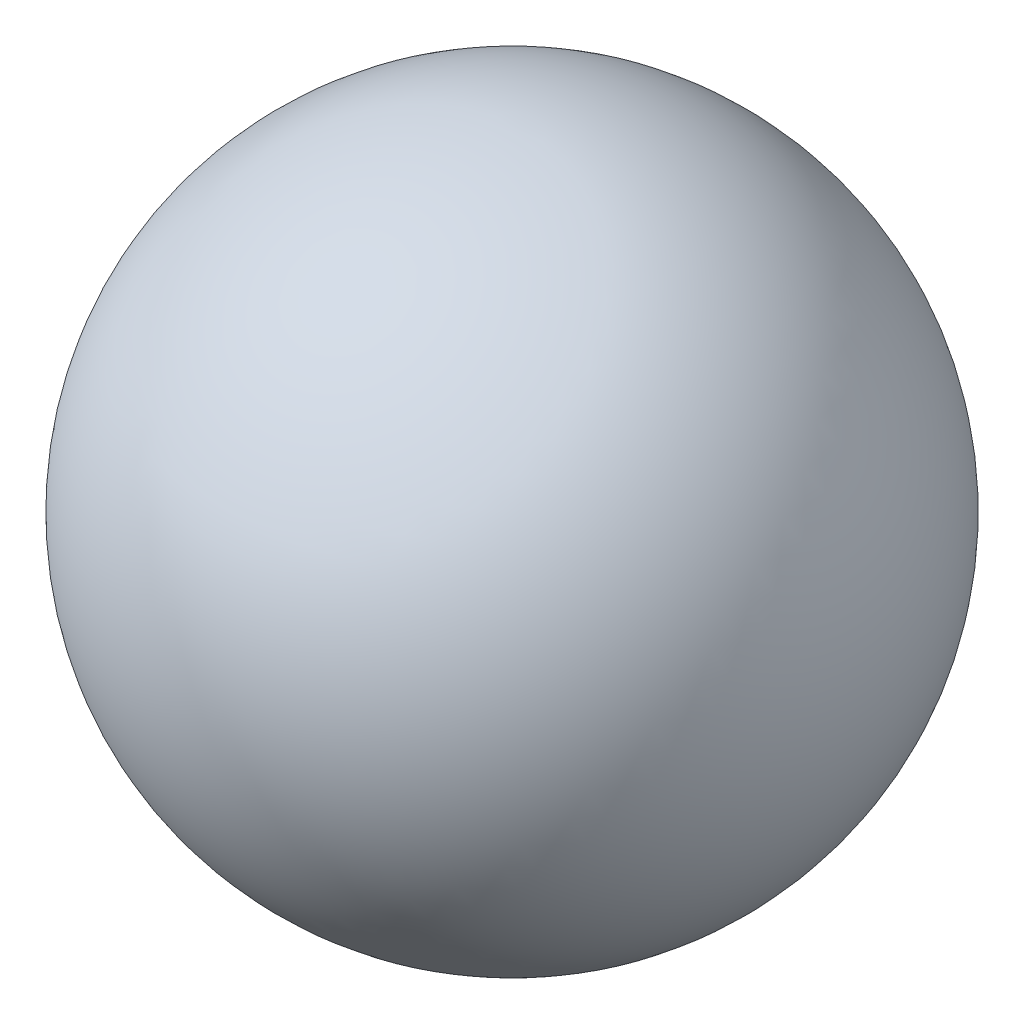
SolidWorks part; units mm, degrees
ref_plane "Front" through (0, 0, 0) normal (0, 0, 1) x (1, 0, 0)
ref_plane "Top" through (0, 0, 0) normal (0, 1, 0) x (1, 0, 0)
ref_plane "Right" through (0, 0, 0) normal (1, 0, 0) x (0, 0, -1)
sketch "Sketch1" plane through (0, 0, 0) normal (0, 0, 1) x (1, 0, 0)
  line L0 (-6, 6) -> (6, 6)
  line L1 (-6, 0) -> (6, 0)
  line L2 (-6, 0) -> (-6, 18)
  line L3 (-6, 18) -> (6, 18)
  line L4 (6, 0) -> (6, 18)
  line L5 (-6, 18) -> (6, 6)
  line L6 (-6, 15) -> (6, 15)
  line L7 (-6, 9) -> (6, 9)
  circle A0 centre (0, 12) radius 3.5
  dimension "D4" = 7
  dimension "D1" = 18
  dimension "D2" = 12
  dimension "D3" = 12
  dimension "D5" = 3
  dimension "D6" = 3
sketch "Sketch2" plane through (0, 0, 0) normal (0, 0, 1) x (1, 0, 0)
  line L0 (0, 15.5) -> (0, 8.5)
  circle A0 centre (0, 12) radius 3.5 construction
  arc A1 (0, 8.5) -> (0, 15.5) centre (0, 12) ccw
revolve "Revolve1" add sketch "Sketch2" angle 360 about L0
